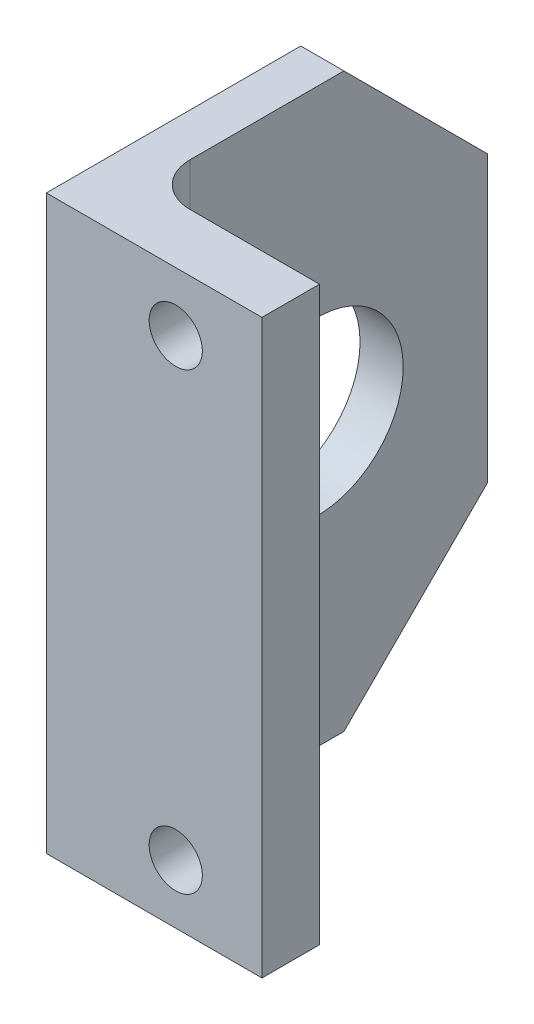
SolidWorks part; units mm, degrees
ref_plane "Front Plane" through (0, 0, 0) normal (0, 0, 1) x (1, 0, 0)
ref_plane "Top Plane" through (0, 0, 0) normal (0, 1, 0) x (1, 0, 0)
ref_plane "Right Plane" through (0, 0, 0) normal (1, 0, 0) x (0, 0, -1)
sketch "Sketch1" plane through (0, 0, 0) normal (0, 1, 0) x (1, 0, 0)
  line L0 (0, 0) -> (0, 27.7)
  line L1 (0, 27.7) -> (3, 27.7)
  line L2 (3, 27.7) -> (3, 4)
  line L3 (3, 4) -> (15, 4)
  line L4 (15, 4) -> (15, 0)
  line L5 (15, 0) -> (0, 0)
  dimension "D1" = 12
  dimension "D2" = 27.7
  dimension "D3" = 4
  dimension "D4" = 3
extrude "Boss-Extrude1" add sketch "Sketch1" along normal blind 39.8
sketch "Sketch2" plane through (0, 0, -4) normal (0, 0, -1) x (-1, 0, 0)
  line L0 (-15, 19.9) -> (-3, 19.9) construction
  line L1 (-15, 39.8) -> (-15, 0) construction
  line L2 (-3, 39.8) -> (-3, 0) construction
  line L3 (-9, 39.8) -> (-9, 0) construction
  line L4 (-15, 39.8) -> (-3, 39.8) construction
  line L5 (-15, 0) -> (-3, 0) construction
  circle A0 centre (-9, 35.7) radius 1.85
  circle A1 centre (-9, 4.1) radius 1.85
  dimension "D2" = 3.7
  dimension "D1" = 15.8
extrude "Cut-Extrude1" cut sketch "Sketch2" against normal blind 39.8
sketch "Sketch3" plane through (3, 0, 0) normal (1, 0, 0) x (0, 0, -1)
  line L0 (15.85, 39.8) -> (15.85, 0) construction
  line L1 (4, 39.8) -> (27.7, 39.8) construction
  line L2 (4, 0) -> (27.7, 0) construction
  circle A0 centre (15.85, 19.9) radius 5.975
  dimension "D1" = 11.95
extrude "Cut-Extrude2" cut sketch "Sketch3" against normal blind 39.8
chamfer "Chamfer1" distance 10 angle 45 2 edges at (1.5, 0, -27.7) (1.5, 39.8, -27.7)
fillet "Fillet1" radius 3 1 edges at (3, 19.9, -4)
